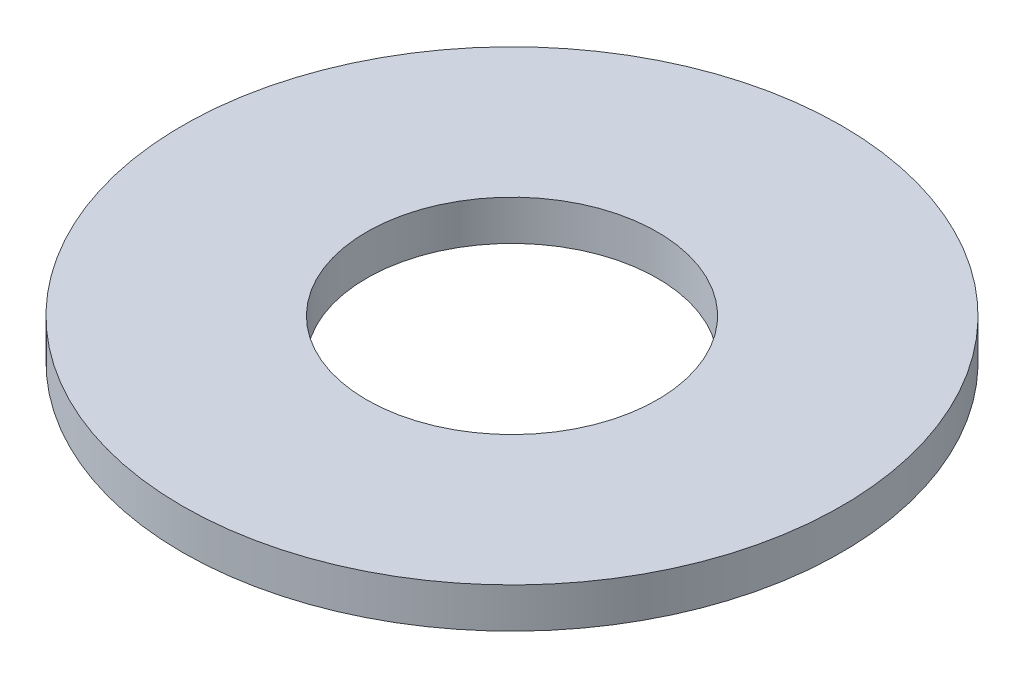
SolidWorks part; units mm, degrees
ref_plane "Front Plane" through (0, 0, 0) normal (0, 0, 1) x (1, 0, 0)
ref_plane "Top Plane" through (0, 0, 0) normal (0, 1, 0) x (1, 0, 0)
ref_plane "Right Plane" through (0, 0, 0) normal (1, 0, 0) x (0, 0, -1)
sketch "Sketch1" plane through (0, 0, 0) normal (0, 1, 0) x (1, 0, 0)
  circle A0 centre (0, 0) radius 25.5
  dimension "D1" = 51
extrude "Boss-Extrude1" add sketch "Sketch1" along normal blind 3.1
sketch "Sketch2" plane through (0, 3.1, 0) normal (0, 1, 0) x (1, 0, 0)
  circle A0 centre (0, 0) radius 11.25
  dimension "D1" = 22.5
extrude "Cut-Extrude1" cut sketch "Sketch2" against normal blind 3.1
